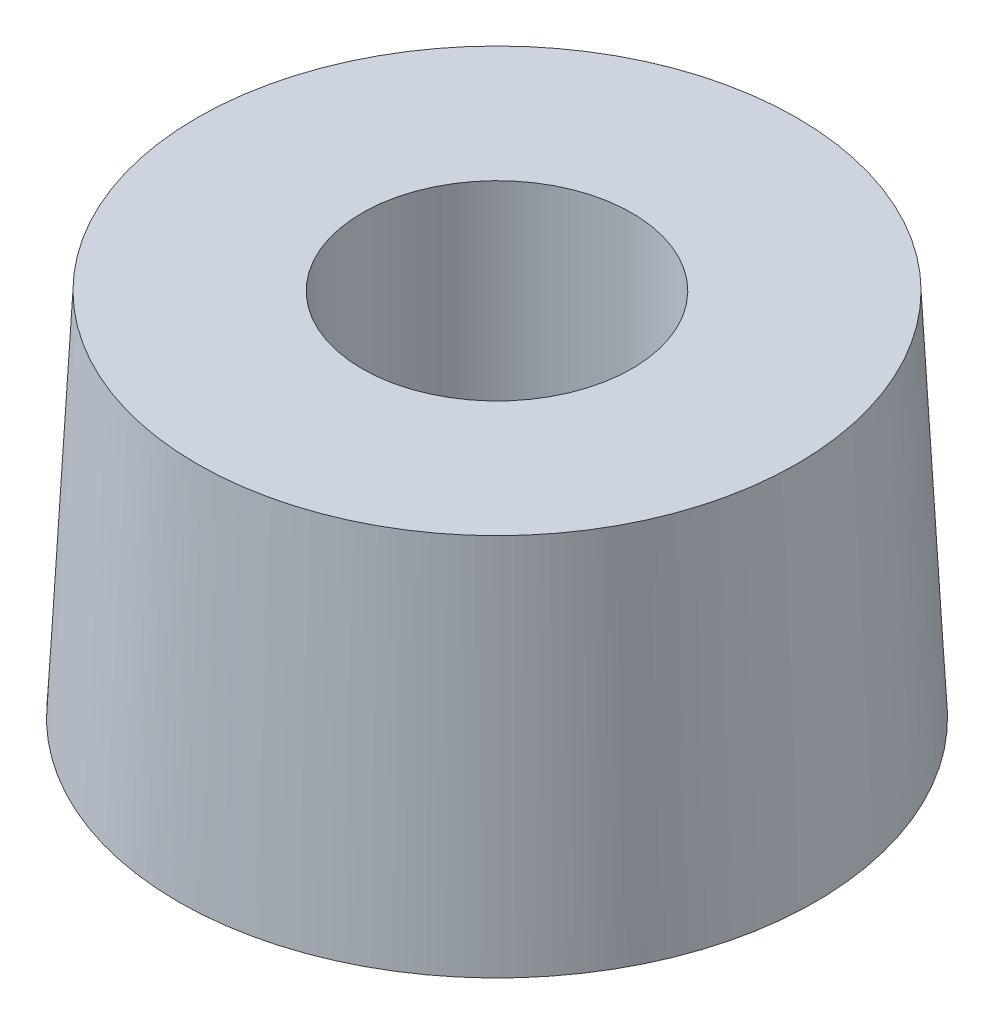
SolidWorks part; units mm, degrees
ref_plane "前视基准面" through (0, 0, 0) normal (0, 0, 1) x (1, 0, 0)
ref_plane "上视基准面" through (0, 0, 0) normal (0, 1, 0) x (1, 0, 0)
ref_plane "右视基准面" through (0, 0, 0) normal (1, 0, 0) x (0, 0, -1)
sketch "草图1" plane through (0, 0, 0) normal (0, 1, 0) x (1, 0, 0)
  circle A0 centre (0, 0) radius 12.75
  dimension "D1" = 25.5
sketch "草图2" plane through (0, 0, 0) normal (0, 0, 1) x (1, 0, 0)
  line L0 (0, 0) -> (0, 14.8)
  dimension "D1" = 14.8
ref_plane "基准面1" through (0, 14.8, 0) normal (0, 1, 0) x (1, 0, 0)
sketch "草图3" plane through (0, 14.8, 0) normal (0, 1, 0) x (1, 0, 0)
  circle A0 centre (0, 0) radius 12
  dimension "D1" = 24
loft "放样1" add profiles "草图3", "草图1"
sketch "草图4" plane through (0, 14.8, 0) normal (0, 1, 0) x (1, 0, 0)
  circle A0 centre (0, 0) radius 5.4
  dimension "D1" = 10.8
extrude "切除-拉伸1" cut sketch "草图4" against normal through all
